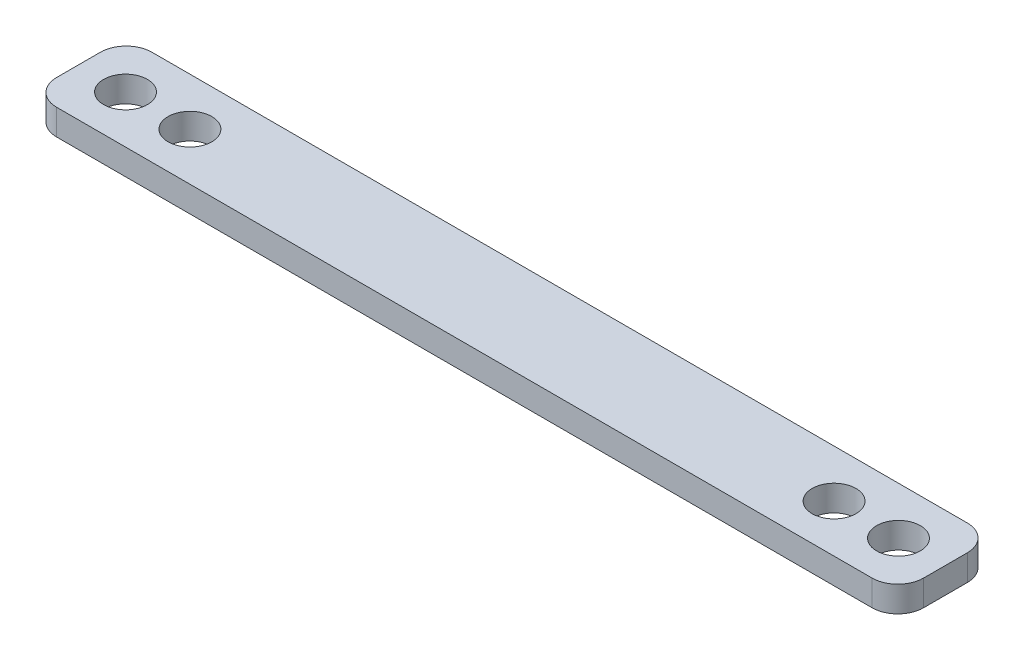
SolidWorks part; units mm, degrees
ref_plane "前视基准面" through (0, 0, 0) normal (0, 0, 1) x (1, 0, 0)
ref_plane "上视基准面" through (0, 0, 0) normal (0, 1, 0) x (1, 0, 0)
ref_plane "右视基准面" through (0, 0, 0) normal (1, 0, 0) x (0, 0, -1)
other "Configuration Table"
sketch "草图1" plane through (0, 0, 0) normal (0, 1, 0) x (1, 0, 0)
  line L0 (0.1939, -0.2441) -> (0.1939, 8.5567) construction
  line L6 (31.8439, 4.8668) -> (-31.4561, 4.8668)
  line L7 (30.1939, 1.1668) -> (-29.8061, 1.1668)
  line L8 (33.8439, 2.8668) -> (33.8439, -0.5332)
  line L9 (31.8439, -2.5332) -> (-31.4561, -2.5332)
  line L10 (-33.4561, 2.8668) -> (-33.4561, -0.5332)
  line L11 (33.8439, 4.8668) -> (-33.4561, -2.5332) construction
  line L12 (33.8439, -2.5332) -> (-33.4561, 4.8668) construction
  circle A0 centre (-29.8061, 1.1668) radius 1.7
  circle A1 centre (30.1939, 1.1668) radius 1.7
  circle A2 centre (-24.8061, 1.1668) radius 1.7
  circle A3 centre (25.1939, 1.1668) radius 1.7
  arc A4 (33.8439, -0.5332) -> (31.8439, -2.5332) centre (31.8439, -0.5332) cw
  arc A5 (31.8439, 4.8668) -> (33.8439, 2.8668) centre (31.8439, 2.8668) cw
  arc A6 (-31.4561, -2.5332) -> (-33.4561, -0.5332) centre (-31.4561, -0.5332) cw
  arc A7 (-31.4561, 4.8668) -> (-33.4561, 2.8668) centre (-31.4561, 2.8668) ccw
  point P0 (0, 0)
  point P1 (0.1939, 1.1668)
  point P11 (0.1939, 1.1668)
  dimension "D2" = 5
  dimension "D5" = 2
  dimension "D1" = 30
  dimension "D3" = 67.3
  dimension "D4" = 7.4
extrude "凸台-拉伸1" add sketch "草图1" along normal blind 2
